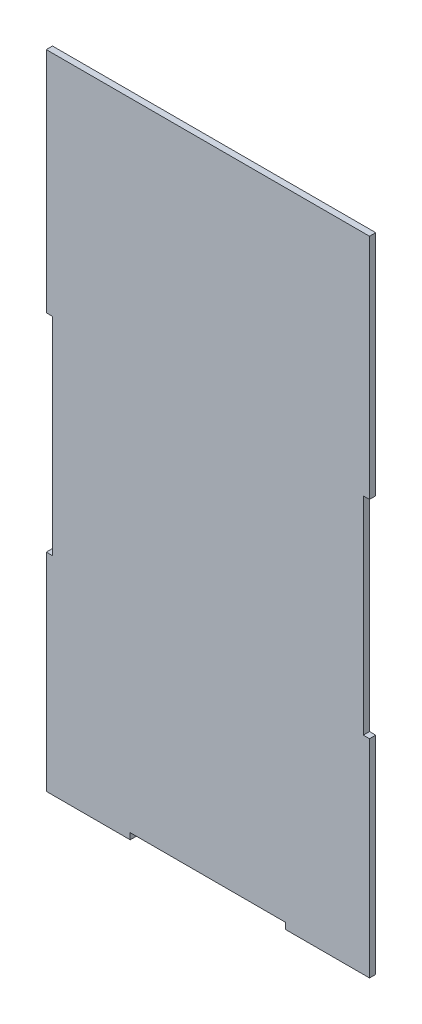
SolidWorks part; units mm, degrees
ref_plane "Alzado" through (0, 0, 0) normal (0, 0, 1) x (1, 0, 0)
ref_plane "Planta" through (0, 0, 0) normal (0, 1, 0) x (1, 0, 0)
ref_plane "Vista lateral" through (0, 0, 0) normal (1, 0, 0) x (0, 0, -1)
sketch "Croquis1" plane through (0, 0, 0) normal (0, 0, 1) x (1, 0, 0)
  line L0 (0, 200) -> (0, 310)
  line L1 (0, 0) -> (40.5, 0)
  line L2 (0, 0) -> (0, 100)
  line L3 (0, 310) -> (156, 310)
  line L4 (156, 0) -> (156, 100)
  line L5 (0, 200) -> (3, 200)
  line L7 (0, 100) -> (3, 100)
  line L8 (3, 200) -> (3, 100)
  line L9 (156, 100) -> (153, 100)
  line L11 (156, 200) -> (153, 200)
  line L12 (153, 100) -> (153, 200)
  line L14 (40.5, 0) -> (40.5, 3)
  line L15 (40.5, 3) -> (115.5, 3)
  line L16 (115.5, 0) -> (115.5, 3)
  line L17 (156, 200) -> (156, 310)
  line L18 (115.5, 0) -> (156, 0)
  dimension "D1" = 156
  dimension "D2" = 310
  dimension "D3" = 100
  dimension "D4" = 100
  dimension "D5" = 100
  dimension "D6" = 100
  dimension "D7" = 3
  dimension "D8" = 3
  dimension "D9" = 75
  dimension "D10" = 40.5
  dimension "D11" = 3
extrude "Saliente-Extruir1" add sketch "Croquis1" along normal blind 3
